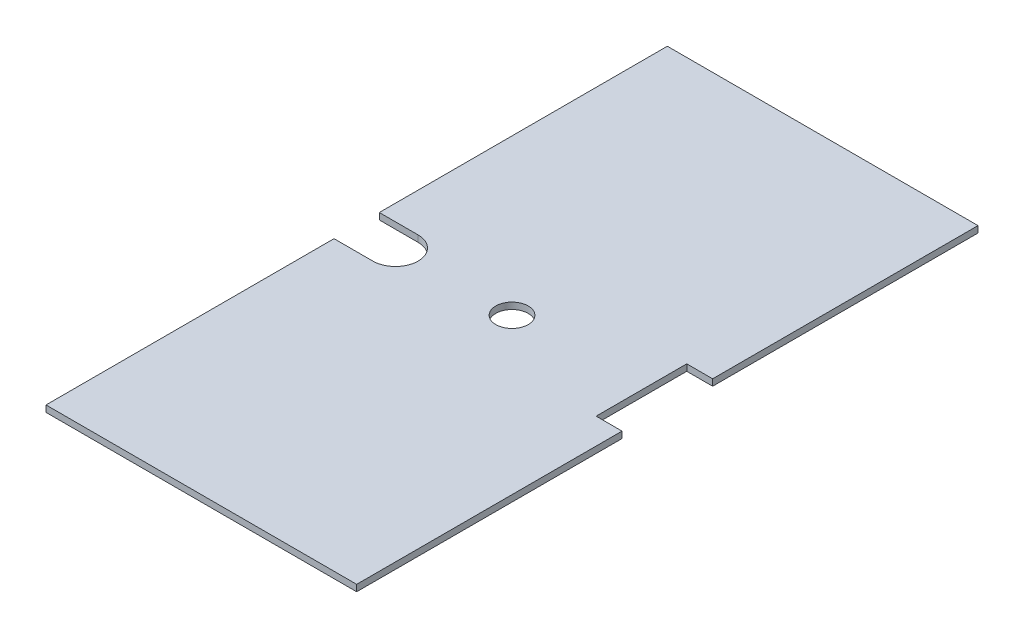
SolidWorks part; units mm, degrees
material "Malleable Cast Iron"
ref_plane "Front Plane" through (0, 0, 0) normal (0, 0, 1) x (1, 0, 0)
ref_plane "Top Plane" through (0, 0, 0) normal (0, 1, 0) x (1, 0, 0)
ref_plane "Right Plane" through (0, 0, 0) normal (1, 0, 0) x (0, 0, -1)
sketch "Sketch1" plane through (0, 0, 0) normal (0, 1, 0) x (1, 0, 0)
  line L0 (-304.8, 609.6) -> (304.8, -609.6) construction
  line L1 (-304.8, 609.6) -> (304.8, 609.6)
  line L2 (-304.8, 609.6) -> (-304.8, -609.6)
  line L3 (-304.8, -609.6) -> (304.8, -609.6)
  line L4 (304.8, 609.6) -> (304.8, -609.6)
  dimension "D1" = 609.6
  dimension "D2" = 1219.2
extrude "Boss-Extrude1" add sketch "Sketch1" along normal blind 12.7
sketch "Sketch2" plane through (0, 12.7, 0) normal (0, 1, 0) x (1, 0, 0)
  line L0 (304.8, 609.6) -> (-304.8, 609.6) construction
  line L1 (-304.8, 609.6) -> (-304.8, -609.6) construction
  circle A0 centre (-292.1, 596.9) radius 3.175
  dimension "D1" = 6.35
  dimension "D2" = 12.7
  dimension "D3" = 12.7
extrude "Cut-Extrude1" [suppressed] cut sketch "Sketch2" against normal through all
pattern_linear "LPattern1" [suppressed] count 24 spacing 25.4 count 48 spacing 25.4
sketch "Sketch3" plane through (0, 12.7, 0) normal (0, 1, 0) x (-1, 0, 0)
  circle A0 centre (-152.8179, 0) radius 31.75
  point P2 (-50.9733, 0)
  dimension "D1" = 63.5
sketch "Sketch6" plane through (0, 12.7, 0) normal (0, 1, 0) x (-1, 0, 0)
  circle A0 centre (0, 0) radius 31.75
  point P2 (0, 0)
  dimension "D1" = 63.5
extrude "Cut-Extrude3" cut sketch "Sketch6" against normal through all
ref_plane "Plane1" through (304.8, 0, 609.6) normal (0, 0, -1) x (-1, 0, 0)
sketch "Sketch8" plane through (0, 12.7, 0) normal (0, 1, 0) x (1, 0, 0)
  line L0 (0, 0) -> (669.9261, 0) construction
  line L1 (669.9261, 88.9) -> (254, 88.9)
  line L2 (669.9261, 88.9) -> (669.9261, -88.9)
  line L3 (669.9261, -88.9) -> (254, -88.9)
  line L4 (254, 88.9) -> (254, -88.9)
  circle A0 centre (0, 0) radius 31.75 construction
  dimension "D1" = 177.8
  dimension "D2" = 254
extrude "Cut-Extrude4" cut sketch "Sketch8" against normal through all
sketch "Sketch10" plane through (0, 12.7, 0) normal (0, 1, 0) x (1, 0, 0)
  line L0 (-228.6, 0) -> (0.6864, 0) construction
  line L1 (-228.6, -44.45) -> (-409.0182, -44.45)
  line L2 (-228.6, -44.45) -> (-228.6, 44.45)
  line L3 (-228.6, 44.45) -> (-409.0182, 44.45)
  line L4 (-409.0182, -44.45) -> (-409.0182, 44.45)
  point P6 (-228.6, 0)
  dimension "D1" = 88.9
extrude "Cut-Extrude7" cut sketch "Sketch10" against normal through all
sketch "Sketch14" plane through (0, 12.7, 0) normal (0, 1, 0) x (1, 0, 0)
  line L0 (-228.6, -44.45) -> (-228.6, 44.45) construction
  circle A0 centre (-228.6, 0) radius 44.45
extrude "Cut-Extrude8" cut sketch "Sketch14" against normal through all
